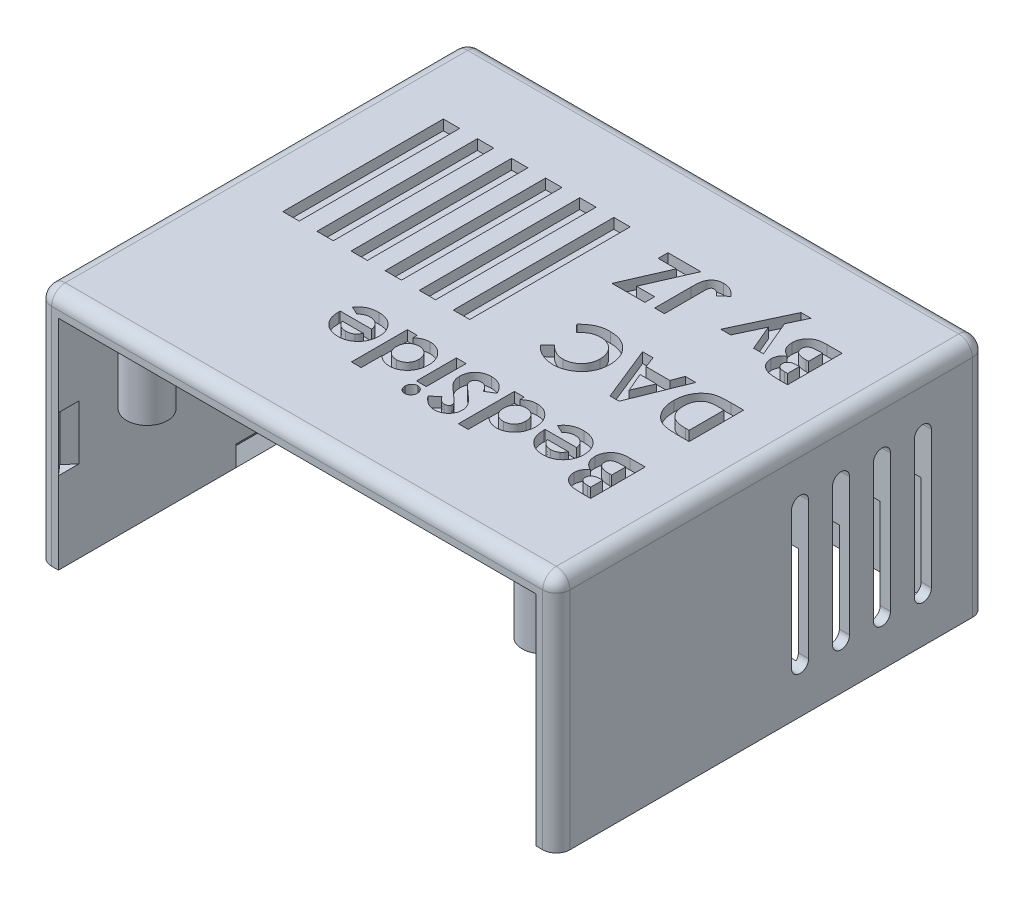
SolidWorks part; units mm, degrees
ref_plane "Front Plane" through (0, 0, 0) normal (0, 0, 1) x (1, 0, 0)
ref_plane "Top Plane" through (0, 0, 0) normal (0, 1, 0) x (1, 0, 0)
ref_plane "Right Plane" through (0, 0, 0) normal (1, 0, 0) x (0, 0, -1)
sketch "Sketch1" plane through (0, 0, 0) normal (0, 1, 0) x (1, 0, 0)
  line L1 (-29, 24.5) -> (29, 24.5) construction
  line L2 (-29, 24.5) -> (-29, -24.5) construction
  line L3 (-29, -24.5) -> (29, -24.5) construction
  line L4 (29, 24.5) -> (29, -24.5) construction
  line L5 (0, -24.5) -> (0, 24.5) construction
  line L6 (-29, 0) -> (29, 0) construction
  point P0 (0, 0)
  dimension "D1" = 58
  dimension "D2" = 49
sketch "Sketch2" plane through (0, 0, 0) normal (0, 1, 0) x (1, 0, 0)
  line L1 (-38, 31.5) -> (38, 31.5)
  line L2 (-38, 31.5) -> (-38, -31.5)
  line L3 (-38, -31.5) -> (38, -31.5)
  line L4 (38, 31.5) -> (38, -31.5)
  line L5 (0, -31.5) -> (0, 31.5) construction
  line L6 (-38, 0) -> (38, 0) construction
  point P0 (0, 0)
  dimension "D1" = 76
  dimension "D2" = 63
extrude "Boss-Extrude1" add sketch "Sketch2" along normal blind 3
sketch "Sketch3" plane through (0, 0, 0) normal (0, -1, 0) x (1, 0, 0)
  circle A0 centre (-29, 24.5) radius 3
  circle A1 centre (-29, 24.5) radius 1.5
  circle A2 centre (29, 24.5) radius 3
  circle A3 centre (29, 24.5) radius 1.5
  circle A4 centre (29, -24.5) radius 3
  circle A5 centre (29, -24.5) radius 1.5
  circle A6 centre (-29, -24.5) radius 3
  circle A7 centre (-29, -24.5) radius 1.5
  dimension "D1" = 3
  dimension "D2" = 6
  dimension "D3" = 3
  dimension "D4" = 6
  dimension "D5" = 3
  dimension "D6" = 6
  dimension "D7" = 3
  dimension "D8" = 6
extrude "Boss-Extrude2" add sketch "Sketch3" along normal blind 12
sketch "Sketch4" plane through (0, 3, 0) normal (0, 1, 0) x (1, 0, 0)
  line L0 (30.8273, -10.3733) -> (-35.581, -10.3733) construction
  text T0 "BedSide\r\nDAC\r\nBy JZ" font "Century Gothic" height 8
extrude "Cut-Extrude3" cut sketch "Sketch4" against normal blind 1.5
sketch "Sketch5" plane through (0, 0, 0) normal (0, -1, 0) x (1, 0, 0)
  line L0 (38, -31.5) -> (-38, -31.5) construction
  line L1 (-38, 31.5) -> (-35, 31.5)
  line L2 (-38, 31.5) -> (-38, -31.5)
  line L3 (-38, -31.5) -> (-35, -31.5)
  line L4 (-35, 31.5) -> (-35, -31.5)
  line L5 (-36.5, -31.5) -> (-36.5, 31.5) construction
  line L6 (-38, 0) -> (-35, 0) construction
  line L7 (-38, 31.5) -> (38, 31.5) construction
  line L8 (38, -31.5) -> (35, -31.5)
  line L9 (38, -31.5) -> (38, 31.5)
  line L10 (38, 31.5) -> (35, 31.5)
  line L11 (35, -31.5) -> (35, 31.5)
  line L12 (36.5, 31.5) -> (36.5, -31.5) construction
  line L13 (38, 0) -> (35, 0) construction
  point P306 (36.5, 0)
  point P528 (-36.5, 0)
  dimension "D1" = 3
  dimension "D2" = 3
extrude "Boss-Extrude3" add sketch "Sketch5" along normal blind 32
sketch "Sketch6" plane through (0, 0, 0) normal (0, -1, 0) x (1, 0, 0)
  line L0 (35, 31.5) -> (35, -31.5) construction
  line L1 (-35, -31.5) -> (35, -31.5)
  line L2 (-35, -31.5) -> (-35, -28.5)
  line L3 (-35, -28.5) -> (35, -28.5)
  line L4 (35, -31.5) -> (35, -28.5)
  line L5 (0, -28.5) -> (0, -31.5) construction
  line L6 (-35, -30) -> (35, -30) construction
  point P212 (0, -30)
  dimension "D1" = 3
extrude "Boss-Extrude4" add sketch "Sketch6" along normal blind 32
sketch "Sketch8" plane through (38, 0, 0) normal (1, 0, 0) x (0, 0, -1)
  line L0 (4.2401, -5.1154) -> (4.2401, -25.2189) construction
  line L1 (5.4901, -5.1154) -> (5.4901, -25.2189)
  line L2 (2.9901, -5.1154) -> (2.9901, -25.2189)
  line L3 (10.2401, -5.1154) -> (10.2401, -25.2189) construction
  line L4 (11.4901, -5.1154) -> (11.4901, -25.2189)
  line L5 (8.9901, -5.1154) -> (8.9901, -25.2189)
  line L6 (16.2401, -5.1154) -> (16.2401, -25.2189) construction
  line L7 (17.4901, -5.1154) -> (17.4901, -25.2189)
  line L8 (14.9901, -5.1154) -> (14.9901, -25.2189)
  line L9 (22.2401, -5.1154) -> (22.2401, -25.2189) construction
  line L10 (23.4901, -5.1154) -> (23.4901, -25.2189)
  line L11 (20.9901, -5.1154) -> (20.9901, -25.2189)
  arc A0 (5.4901, -5.1154) -> (2.9901, -5.1154) centre (4.2401, -5.1154) ccw
  arc A1 (2.9901, -25.2189) -> (5.4901, -25.2189) centre (4.2401, -25.2189) ccw
  arc A2 (11.4901, -5.1154) -> (8.9901, -5.1154) centre (10.2401, -5.1154) ccw
  arc A3 (8.9901, -25.2189) -> (11.4901, -25.2189) centre (10.2401, -25.2189) ccw
  arc A4 (17.4901, -5.1154) -> (14.9901, -5.1154) centre (16.2401, -5.1154) ccw
  arc A5 (14.9901, -25.2189) -> (17.4901, -25.2189) centre (16.2401, -25.2189) ccw
  arc A6 (23.4901, -5.1154) -> (20.9901, -5.1154) centre (22.2401, -5.1154) ccw
  arc A7 (20.9901, -25.2189) -> (23.4901, -25.2189) centre (22.2401, -25.2189) ccw
  point P2 (4.2401, -15.1671)
  point P10 (10.2401, -15.1671)
  point P17 (16.2401, -15.1671)
  point P24 (22.2401, -15.1671)
  dimension "D1" = 2.5
  dimension "D2" = 4
extrude "Cut-Extrude5" cut sketch "Sketch8" against normal up to surface (3 mm away) up to face at (35, -16, 1.5)
sketch "Sketch9" plane through (-38, 0, 0) normal (-1, 0, 0) x (0, 0, 1)
  line L2 (-11.4901, -5.1154) -> (-11.4901, -25.2189)
  line L3 (-8.9901, -25.2189) -> (-8.9901, -5.1154)
  line L4 (-11.4901, -5.1154) -> (-11.4901, -25.2189)
  line L5 (-8.9901, -25.2189) -> (-8.9901, -5.1154)
  line L6 (-5.4901, -5.1154) -> (-5.4901, -25.2189)
  line L7 (-2.9901, -25.2189) -> (-2.9901, -5.1154)
  line L8 (-5.4901, -5.1154) -> (-5.4901, -25.2189)
  line L9 (-2.9901, -25.2189) -> (-2.9901, -5.1154)
  line L10 (-23.4901, -5.1154) -> (-23.4901, -25.2189)
  line L11 (-20.9901, -25.2189) -> (-20.9901, -5.1154)
  line L12 (-23.4901, -5.1154) -> (-23.4901, -25.2189)
  line L13 (-20.9901, -25.2189) -> (-20.9901, -5.1154)
  line L14 (-17.4901, -5.1154) -> (-17.4901, -25.2189)
  line L15 (-14.9901, -25.2189) -> (-14.9901, -5.1154)
  line L16 (-17.4901, -5.1154) -> (-17.4901, -25.2189)
  line L17 (-14.9901, -25.2189) -> (-14.9901, -5.1154)
  arc A2 (-11.4901, -25.2189) -> (-8.9901, -25.2189) centre (-10.2401, -25.2189) ccw
  arc A3 (-8.9901, -5.1154) -> (-11.4901, -5.1154) centre (-10.2401, -5.1154) ccw
  arc A4 (-11.4901, -25.2189) -> (-8.9901, -25.2189) centre (-10.2401, -25.2189) ccw
  arc A5 (-8.9901, -5.1154) -> (-11.4901, -5.1154) centre (-10.2401, -5.1154) ccw
  arc A6 (-5.4901, -25.2189) -> (-2.9901, -25.2189) centre (-4.2401, -25.2189) ccw
  arc A7 (-2.9901, -5.1154) -> (-5.4901, -5.1154) centre (-4.2401, -5.1154) ccw
  arc A8 (-5.4901, -25.2189) -> (-2.9901, -25.2189) centre (-4.2401, -25.2189) ccw
  arc A9 (-2.9901, -5.1154) -> (-5.4901, -5.1154) centre (-4.2401, -5.1154) ccw
  arc A10 (-23.4901, -25.2189) -> (-20.9901, -25.2189) centre (-22.2401, -25.2189) ccw
  arc A11 (-20.9901, -5.1154) -> (-23.4901, -5.1154) centre (-22.2401, -5.1154) ccw
  arc A12 (-23.4901, -25.2189) -> (-20.9901, -25.2189) centre (-22.2401, -25.2189) ccw
  arc A13 (-20.9901, -5.1154) -> (-23.4901, -5.1154) centre (-22.2401, -5.1154) ccw
  arc A14 (-17.4901, -25.2189) -> (-14.9901, -25.2189) centre (-16.2401, -25.2189) ccw
  arc A15 (-14.9901, -5.1154) -> (-17.4901, -5.1154) centre (-16.2401, -5.1154) ccw
  arc A16 (-17.4901, -25.2189) -> (-14.9901, -25.2189) centre (-16.2401, -25.2189) ccw
  arc A17 (-14.9901, -5.1154) -> (-17.4901, -5.1154) centre (-16.2401, -5.1154) ccw
  dimension "D1" = 0
  dimension "D2" = 0
  dimension "D3" = 0
  dimension "D4" = 0
extrude "Cut-Extrude6" cut sketch "Sketch9" against normal up to surface (3 mm away) up to face at (-35, -16, 1.5)
ref_plane "Plane2" through (0, -16, 0) normal (0, -1, 0) x (-1, 0, 0)
sketch "Sketch10" plane through (0, -16, 0) normal (0, -1, 0) x (-1, 0, 0)
  line L0 (-35, -28.5) -> (-36.3, -30)
  line L1 (-35, -31.5) -> (-35, 28.5) construction
  line L2 (-36.3, -30) -> (-35, -31.5)
  line L3 (-35, -31.5) -> (-35, -28.5)
  line L4 (-38, -31.5) -> (-35, -31.5) construction
  line L5 (0, 0) -> (0, -29.2177) construction
  line L6 (35, -31.5) -> (35, -28.5)
  line L7 (36.3, -30) -> (35, -31.5)
  line L8 (35, -28.5) -> (36.3, -30)
  dimension "D1" = 1.5
  dimension "D2" = 3
  dimension "D3" = 1.3
extrude "Cut-Extrude7" cut sketch "Sketch10" against normal mid plane 8
ref_plane "Plane4" through (0, 0, 1.5) normal (0, 0, 1) x (1, 0, 0)
sketch "Sketch11" plane through (0, 0, 1.5) normal (0, 0, 1) x (1, 0, 0)
  line L0 (-35, -32) -> (-36.3, -30.5)
  line L1 (-36.3, -30.5) -> (-35, -29)
  line L2 (-35, -32) -> (-35, 0) construction
  line L3 (-35, -29) -> (-35, -32)
  line L4 (-35, -32) -> (-38, -32) construction
  line L5 (-35, -32) -> (-35, -20) construction
  line L6 (0, 0) -> (0, -26.3935) construction
  line L7 (35, -29) -> (35, -32)
  line L8 (36.3, -30.5) -> (35, -29)
  line L9 (35, -32) -> (36.3, -30.5)
  dimension "D1" = 1.5
  dimension "D2" = 3
  dimension "D3" = 1.3
extrude "Cut-Extrude8" cut sketch "Sketch11" against normal mid plane 8
sketch "Sketch12" plane through (0, 0, 0) normal (1, 0, 0) x (0, 0, -1)
  line L0 (28.5, -32) -> (29.8, -30.5)
  line L1 (29.8, -30.5) -> (28.5, -29)
  line L3 (28.5, -29) -> (28.5, -32)
  line L4 (31.5, -32) -> (-31.5, -32) construction
  line L5 (28.5, -32) -> (28.5, 0) construction
  dimension "D1" = 3
  dimension "D2" = 1.5
  dimension "D3" = 1.3
extrude "Cut-Extrude9" cut sketch "Sketch12" against normal mid plane 8
fillet "Fillet1" radius 2 8 edges at (0, 3, 31.5) (-38, 3, 0) (38, -14.5, 31.5) (-38, -14.5, 31.5) (-38, -14.5, -31.5) (38, -14.5, -31.5) (0, 3, -31.5) (38, 3, 0)
sketch "Sketch13" plane through (0, 3, 0) normal (0, 1, 0) x (1, 0, 0)
  line L0 (-4.0822, 19.011) -> (-1.6813, 19.011)
  line L1 (-1.6813, 19.011) -> (-1.6813, -4.5202)
  line L2 (-1.6813, -4.5202) -> (-4.0822, -4.5202)
  line L3 (-4.0822, -4.5202) -> (-4.0822, 19.011)
  line L4 (-9.0822, 19.011) -> (-6.6813, 19.011)
  line L5 (-9.0822, -4.5202) -> (-9.0822, 19.011)
  line L6 (-6.6813, -4.5202) -> (-9.0822, -4.5202)
  line L7 (-6.6813, 19.011) -> (-6.6813, -4.5202)
  line L8 (-14.0822, 19.011) -> (-11.6813, 19.011)
  line L9 (-14.0822, -4.5202) -> (-14.0822, 19.011)
  line L10 (-11.6813, -4.5202) -> (-14.0822, -4.5202)
  line L11 (-11.6813, 19.011) -> (-11.6813, -4.5202)
  line L12 (-19.0822, 19.011) -> (-16.6813, 19.011)
  line L13 (-19.0822, -4.5202) -> (-19.0822, 19.011)
  line L14 (-16.6813, -4.5202) -> (-19.0822, -4.5202)
  line L15 (-16.6813, 19.011) -> (-16.6813, -4.5202)
  line L16 (-24.0822, 19.011) -> (-21.6813, 19.011)
  line L17 (-24.0822, -4.5202) -> (-24.0822, 19.011)
  line L18 (-21.6813, -4.5202) -> (-24.0822, -4.5202)
  line L19 (-21.6813, 19.011) -> (-21.6813, -4.5202)
  line L20 (-29.0822, 19.011) -> (-26.6813, 19.011)
  line L21 (-29.0822, -4.5202) -> (-29.0822, 19.011)
  line L22 (-26.6813, -4.5202) -> (-29.0822, -4.5202)
  line L23 (-26.6813, 19.011) -> (-26.6813, -4.5202)
  dimension "D1" = 6
extrude "Cut-Extrude10" cut sketch "Sketch13" against normal blind 1.5
sketch "Sketch14" plane through (0, -32, 0) normal (0, -1, 0) x (1, 0, 0)
  line L0 (-35, -28.5) -> (-35, -2.5) construction
  line L1 (-35, -28.5) -> (-36.5, -28.5)
  line L2 (-35, -28.5) -> (-35, -5.1476)
  line L3 (-35, -5.1476) -> (-36.5, -5.1476)
  line L4 (-36.5, -28.5) -> (-36.5, -5.1476)
  line L5 (-35.75, -5.1476) -> (-35.75, -28.5) construction
  line L6 (-35, -16.8238) -> (-36.5, -16.8238) construction
  line L7 (35, -28.5) -> (36.5, -28.5)
  line L8 (35, -28.5) -> (35, -5.1476)
  line L9 (35, -5.1476) -> (36.5, -5.1476)
  line L10 (36.5, -28.5) -> (36.5, -5.1476)
  line L11 (35.75, -5.1476) -> (35.75, -28.5) construction
  line L12 (35, -16.8238) -> (36.5, -16.8238) construction
  point P8 (-35, -5.1476)
  point P296 (-35.75, -16.8238)
  point P550 (35.75, -16.8238)
  dimension "D1" = 1.5
  dimension "D2" = 1.5
extrude "Cut-Extrude11" cut sketch "Sketch14" against normal blind 20
